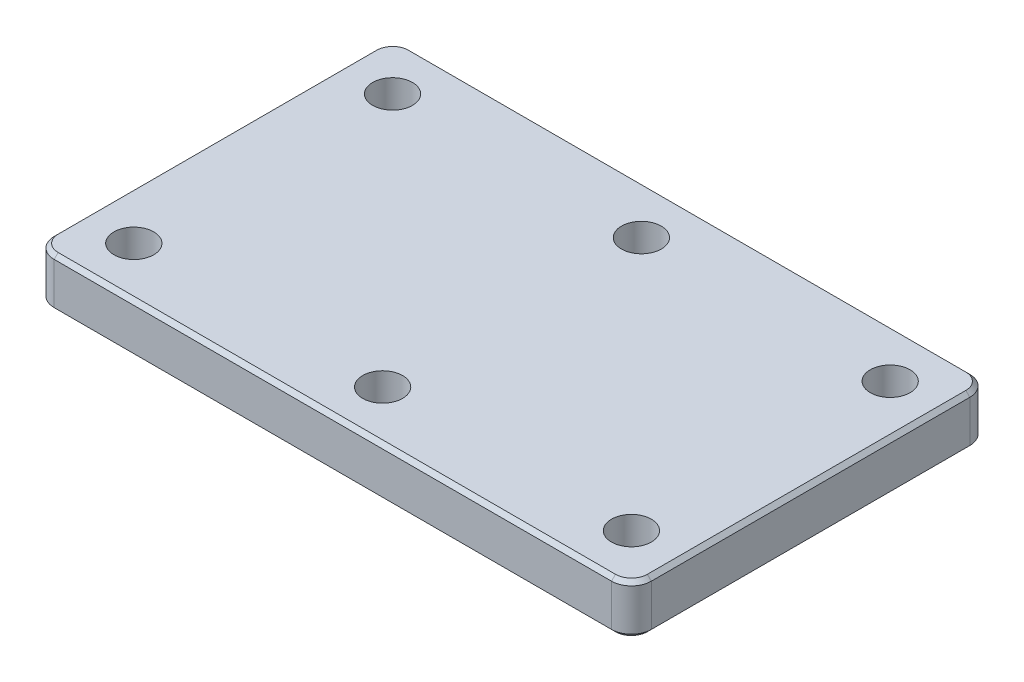
SolidWorks part; units mm, degrees
ref_plane "Front Plane" through (0, 0, 0) normal (0, 0, 1) x (1, 0, 0)
ref_plane "Top Plane" through (0, 0, 0) normal (0, 1, 0) x (1, 0, 0)
ref_plane "Right Plane" through (0, 0, 0) normal (1, 0, 0) x (0, 0, -1)
sketch "Sketch1" plane through (0, 0, 0) normal (0, 1, 0) x (1, 0, 0)
  line L0 (10, 0) -> (290, 0)
  line L1 (300, -10) -> (300, -170)
  line L2 (290, -180) -> (10, -180)
  line L3 (0, -170) -> (0, -10)
  circle A0 centre (25, -25) radius 10
  circle A1 centre (25, -155) radius 10
  circle A2 centre (275, -25) radius 10
  circle A3 centre (275, -155) radius 10
  circle A4 centre (150, -25) radius 10
  circle A5 centre (150, -155) radius 10
  arc A6 (290, -180) -> (300, -170) centre (290, -170) ccw
  arc A7 (300, -10) -> (290, 0) centre (290, -10) ccw
  arc A8 (0, -10) -> (10, 0) centre (10, -10) cw
  arc A9 (10, -180) -> (0, -170) centre (10, -170) cw
  point P25 (0, 0)
  dimension "D1" = 10
extrude "Boss-Extrude1" add sketch "Sketch1" along normal mid plane 25
chamfer "Chamfer1" distance 2 angle 45 16 edges at (297.0711, -12.5, 2.9289) (150, -12.5, 0) (300, -12.5, 90) (2.9289, -12.5, 2.9289) (297.0711, -12.5, 177.0711) (0, -12.5, 90) (150, -12.5, 180) (2.9289, -12.5, 177.0711) (150, 12.5, 0) (2.9289, 12.5, 2.9289) (297.0711, 12.5, 2.9289) (0, 12.5, 90) (300, 12.5, 90) (2.9289, 12.5, 177.0711) (297.0711, 12.5, 177.0711) (150, 12.5, 180)
ref_plane "Plane1" through (0, 0, 90) normal (0, 0, 1) x (1, 0, 0)
ref_plane "Plane2" through (150, 0, 0) normal (-1, 0, 0) x (0, 0, 1)
